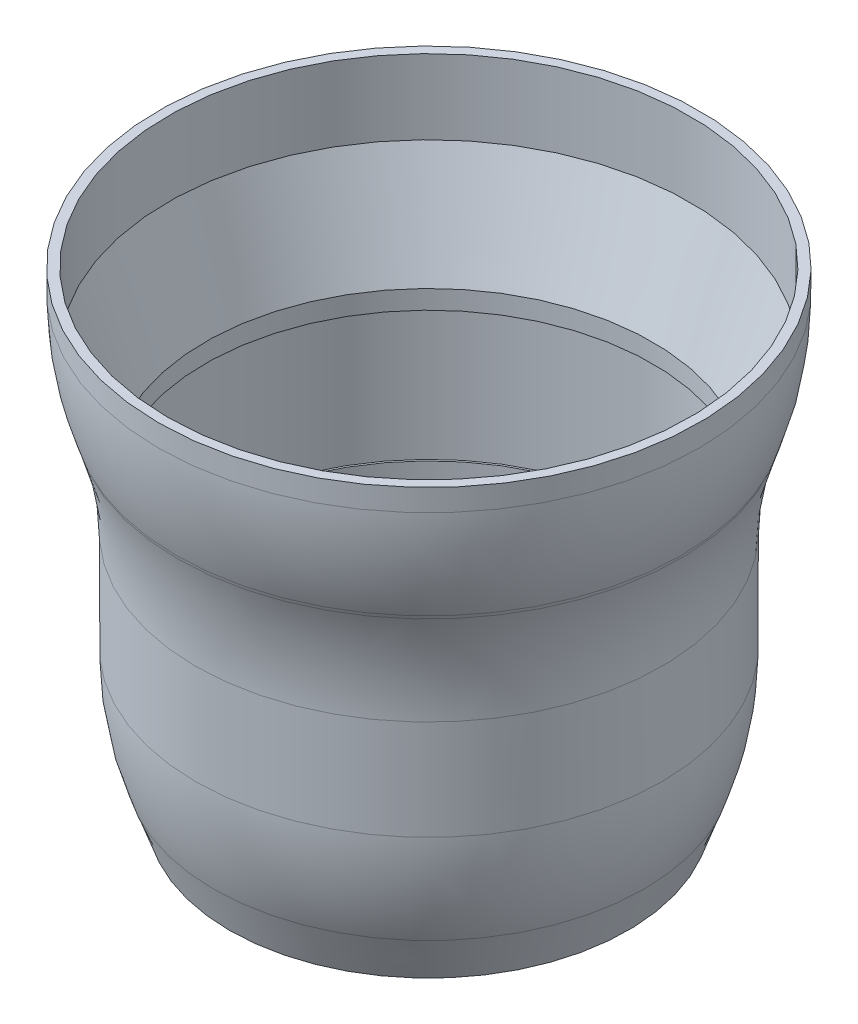
SolidWorks part; units mm, degrees
ref_plane "Front Plane" through (0, 0, 0) normal (0, 0, 1) x (1, 0, 0)
ref_plane "Top Plane" through (0, 0, 0) normal (0, 1, 0) x (1, 0, 0)
ref_plane "Right Plane" through (0, 0, 0) normal (1, 0, 0) x (0, 0, -1)
sketch "Sketch1" plane through (0, 0, 0) normal (1, 0, 0) x (0, 0, -1)
  line L0 (0, 159.947) -> (0, -59.5455) construction
  line L1 (140, 159.947) -> (145, 159.947)
  line L2 (145, 159.947) -> (145, 119.947)
  line L3 (145, 119.947) -> (125, 64.9974)
  line L4 (125, 64.9974) -> (125, -45.0026)
  line L5 (125, -45.0026) -> (106.8015, -95.0026)
  line L6 (106.8015, -95.0026) -> (101.8015, -95.0026)
  line L7 (101.8015, -95.0026) -> (120, -45.0026)
  line L8 (120, -45.0026) -> (120, -15.0871)
  line L9 (120, 64.9974) -> (140, 119.947)
  line L10 (140, 119.947) -> (140, 159.947)
  line L11 (120, 54.9129) -> (120, 64.9974)
  line L12 (120, 54.9129) -> (121, 54.9129)
  line L14 (120, -15.0871) -> (121, -15.0871)
  line L15 (121, 54.9129) -> (121, -15.0871)
  dimension "D1" = 5
  dimension "D2" = 5
  dimension "D3" = 5
  dimension "D4" = 110
  dimension "D5" = 40
  dimension "D6" = 40
  dimension "D7" = 110
  dimension "D8" = 50
  dimension "D9" = 120
  dimension "D10" = 140
  dimension "D11" = 160
  dimension "D12" = 1
  dimension "D13" = 70
revolve "Revolve1" add sketch "Sketch1" angle 360 about L0
fillet "Fillet1" radius 160 3 edges at (0, -45.0026, 125) (0, 64.9974, 125) (0, 119.947, 145)
